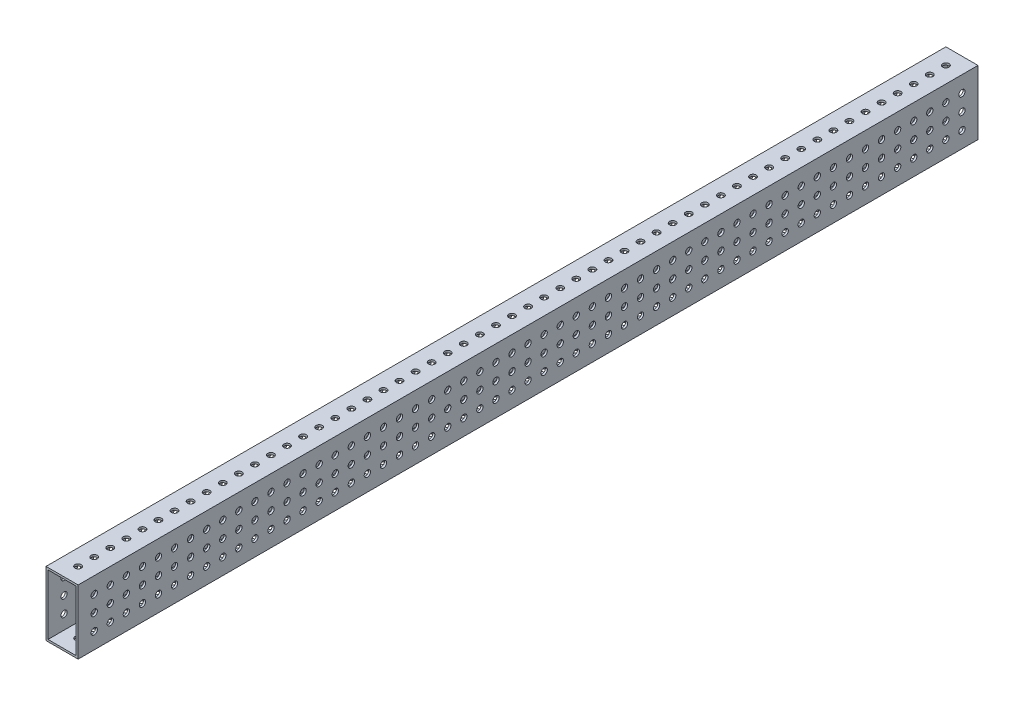
SolidWorks part; units mm, degrees
material "6061-T6 (SS)"
ref_plane "Front Plane" through (0, 0, 0) normal (0, 0, 1) x (1, 0, 0)
ref_plane "Top Plane" through (0, 0, 0) normal (0, 1, 0) x (1, 0, 0)
ref_plane "Right Plane" through (0, 0, 0) normal (1, 0, 0) x (0, 0, -1)
sketch "Sketch1" plane through (0, 0, 0) normal (0, 0, 1) x (1, 0, 0)
  line L0 (1.5875, 1.5875) -> (1.5875, 49.2125)
  line L1 (0, 0) -> (25.4, 0)
  line L2 (0, 0) -> (0, 50.8)
  line L3 (0, 50.8) -> (25.4, 50.8)
  line L4 (25.4, 0) -> (25.4, 50.8)
  line L5 (1.5875, 49.2125) -> (23.8125, 49.2125)
  line L6 (23.8125, 1.5875) -> (23.8125, 49.2125)
  line L7 (1.5875, 1.5875) -> (23.8125, 1.5875)
  dimension "D2" = 50.8
  dimension "D3" = 25.4
  dimension "D1" = 1.5875
extrude "Boss-Extrude1" add sketch "Sketch1" along normal mid plane 711.2
sketch "Sketch2" plane through (0, 0, 0) normal (-1, 0, 0) x (0, 0, 1)
  line L0 (-342.9, 50.8) -> (-342.9, 0) construction
  line L1 (355.6, 50.8) -> (-355.6, 50.8) construction
  line L2 (355.6, 0) -> (-355.6, 0) construction
  line L3 (-355.6, 50.8) -> (-355.6, 0) construction
  circle A0 centre (-342.9, 38.1) radius 2.4892
  circle A1 centre (-342.9, 25.4) radius 2.4892
  circle A2 centre (-342.9, 12.7) radius 2.4892
  dimension "D1" = 4.9784
  dimension "D2" = 12.7
  dimension "D3" = 12.7
  dimension "D4" = 12.7
  dimension "D5" = 12.7
extrude "Cut-Extrude1" cut sketch "Sketch2" against normal through all
pattern_linear "LPattern1" count 55 spacing 12.7 along (0, 0, 1) of "Cut-Extrude1"
sketch "Sketch3" plane through (0, 50.8, 0) normal (0, 1, 0) x (1, 0, 0)
  line L0 (12.7, 355.6) -> (12.7, -355.6) construction
  line L1 (25.4, 355.6) -> (0, 355.6) construction
  line L2 (25.4, -355.6) -> (0, -355.6) construction
  line L3 (25.4, 0) -> (0, 0) construction
  line L4 (25.4, -355.6) -> (25.4, 355.6) construction
  line L5 (0, -355.6) -> (0, 355.6) construction
  circle A0 centre (12.7, 342.9) radius 2.4892
  circle A1 centre (12.7, 330.2) radius 2.4892
  circle A2 centre (12.7, 317.5) radius 2.4892
  circle A3 centre (12.7, 304.8) radius 2.4892
  circle A4 centre (12.7, 292.1) radius 2.4892
  circle A5 centre (12.7, 279.4) radius 2.4892
  circle A6 centre (12.7, 266.7) radius 2.4892
  circle A7 centre (12.7, 254) radius 2.4892
  circle A8 centre (12.7, 241.3) radius 2.4892
  circle A9 centre (12.7, 228.6) radius 2.4892
  circle A10 centre (12.7, 215.9) radius 2.4892
  circle A11 centre (12.7, 203.2) radius 2.4892
  circle A12 centre (12.7, 190.5) radius 2.4892
  circle A13 centre (12.7, 177.8) radius 2.4892
  circle A14 centre (12.7, 165.1) radius 2.4892
  circle A15 centre (12.7, 152.4) radius 2.4892
  circle A16 centre (12.7, 139.7) radius 2.4892
  circle A17 centre (12.7, 127) radius 2.4892
  circle A18 centre (12.7, 114.3) radius 2.4892
  circle A19 centre (12.7, 101.6) radius 2.4892
  circle A20 centre (12.7, 88.9) radius 2.4892
  circle A21 centre (12.7, 76.2) radius 2.4892
  circle A22 centre (12.7, 63.5) radius 2.4892
  circle A23 centre (12.7, 50.8) radius 2.4892
  circle A24 centre (12.7, 38.1) radius 2.4892
  circle A25 centre (12.7, 25.4) radius 2.4892
  circle A26 centre (12.7, 12.7) radius 2.4892
  circle A27 centre (12.7, 0) radius 2.4892
  circle A28 centre (12.7, -12.7) radius 2.4892
  circle A29 centre (12.7, -25.4) radius 2.4892
  circle A30 centre (12.7, -38.1) radius 2.4892
  circle A31 centre (12.7, -50.8) radius 2.4892
  circle A32 centre (12.7, -63.5) radius 2.4892
  circle A33 centre (12.7, -76.2) radius 2.4892
  circle A34 centre (12.7, -88.9) radius 2.4892
  circle A35 centre (12.7, -101.6) radius 2.4892
  circle A36 centre (12.7, -114.3) radius 2.4892
  circle A37 centre (12.7, -127) radius 2.4892
  circle A38 centre (12.7, 349.25) radius 2.1526 construction
  circle A40 centre (12.7, 323.85) radius 2.1526 construction
  circle A41 centre (12.7, 298.45) radius 2.1526 construction
  circle A42 centre (12.7, -349.25) radius 2.1526 construction
  circle A43 centre (12.7, -323.85) radius 2.1526 construction
  circle A44 centre (12.7, -298.45) radius 2.1526 construction
  circle A45 centre (12.7, -139.7) radius 2.4892
  circle A46 centre (12.7, -152.4) radius 2.4892
  circle A47 centre (12.7, -165.1) radius 2.4892
  circle A48 centre (12.7, -177.8) radius 2.4892
  circle A49 centre (12.7, -190.5) radius 2.4892
  circle A50 centre (12.7, -203.2) radius 2.4892
  circle A51 centre (12.7, -215.9) radius 2.4892
  circle A52 centre (12.7, -228.6) radius 2.4892
  circle A53 centre (12.7, -241.3) radius 2.4892
  circle A54 centre (12.7, -254) radius 2.4892
  circle A55 centre (12.7, -266.7) radius 2.4892
  circle A56 centre (12.7, -279.4) radius 2.4892
  circle A57 centre (12.7, -292.1) radius 2.4892
  circle A58 centre (12.7, -304.8) radius 2.4892
  circle A59 centre (12.7, -317.5) radius 2.4892
  circle A60 centre (12.7, -330.2) radius 2.4892
  circle A61 centre (12.7, -342.9) radius 2.4892
  dimension "D1" = 4.9784
  dimension "D5" = 4.3053
  dimension "D2" = 12.7
  dimension "D4" = 12.7
  dimension "D6" = 6.35
  dimension "D8" = 25.4
  dimension "D3" = 55
  dimension "D7" = 3
extrude "Cut-Extrude2" cut sketch "Sketch3" against normal through all
